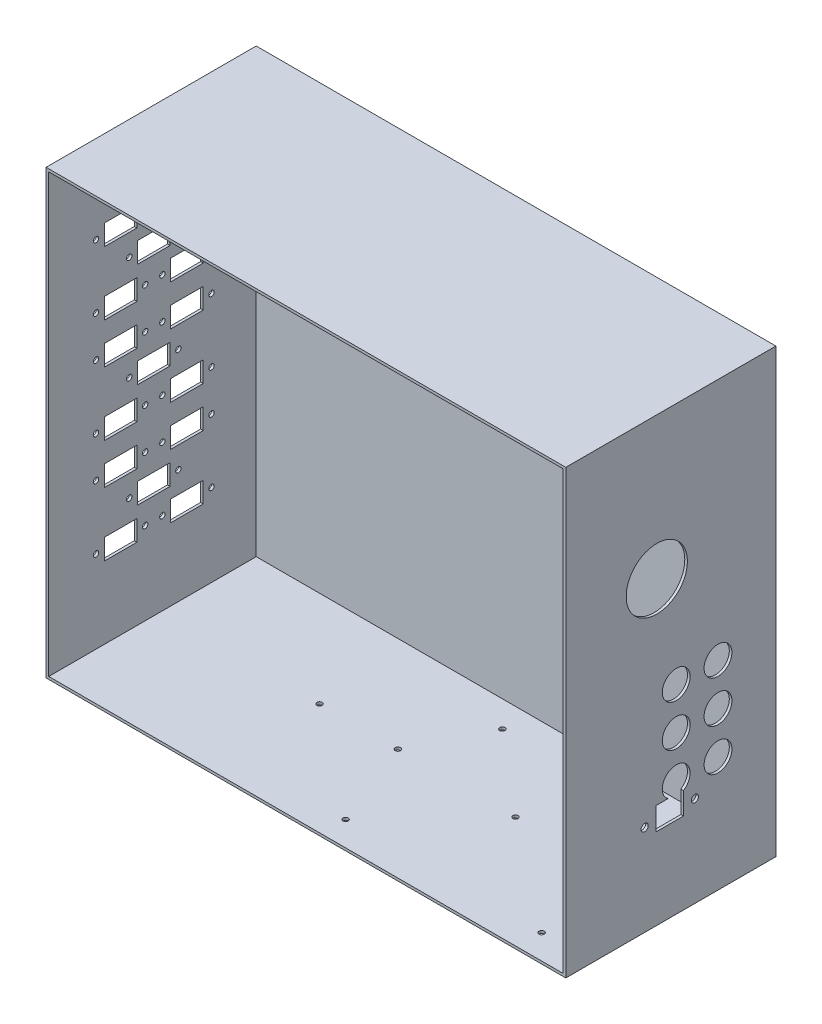
SolidWorks part; units mm, degrees
ref_plane "Front Plane" through (0, 0, 0) normal (0, 0, 1) x (1, 0, 0)
ref_plane "Top Plane" through (0, 0, 0) normal (0, 1, 0) x (1, 0, 0)
ref_plane "Right Plane" through (0, 0, 0) normal (1, 0, 0) x (0, 0, -1)
sketch "Sketch2" plane through (0, 0, 0) normal (0, 0, 1) x (1, 0, 0)
  line L1 (-149.225, 127) -> (149.225, 127)
  line L2 (-149.225, 127) -> (-149.225, -127)
  line L3 (-149.225, -127) -> (149.225, -127)
  line L4 (149.225, 127) -> (149.225, -127)
  line L5 (-149.225, 127) -> (149.225, -127) construction
  line L6 (-149.225, -127) -> (149.225, 127) construction
  point P0 (0, 0)
  dimension "D1" = 298.45
  dimension "D2" = 254
extrude "Boss-Extrude1" add sketch "Sketch2" along normal blind 120.65
shell "Shell1" thickness 1.5
sketch "Sketch3" plane through (149.225, 0, 0) normal (1, 0, 0) x (0, 0, -1)
  circle A0 centre (-57.2397, -60.6921) radius 8
  circle A1 centre (-33.2397, -60.6921) radius 8
  circle A2 centre (-33.2397, -36.6921) radius 8
  circle A3 centre (-33.2397, -12.6921) radius 8
  circle A4 centre (-57.2397, -36.6921) radius 8
  circle A5 centre (-57.2397, -12.6921) radius 8
  dimension "D1" = 16
  dimension "D2" = 2
  dimension "D3" = 3
extrude "PT Connector Cutouts" cut sketch "Sketch3" against normal up to next
sketch "Sketch4" plane through (-149.225, 0, 0) normal (-1, 0, 0) x (0, 0, 1)
  line L0 (41.275, 72.2563) -> (41.275, 84.0563) construction
  line L1 (31.925, 84.0563) -> (31.925, 72.2563)
  line L2 (31.925, 84.0563) -> (50.625, 84.0563)
  line L3 (50.625, 84.0563) -> (50.625, 72.2563)
  line L4 (31.925, 72.2563) -> (50.625, 72.2563)
  line L10 (22.225, -88.9) -> (98.425, -88.9) construction
  line L11 (22.225, -88.9) -> (22.225, 88.9) construction
  line L12 (22.225, 88.9) -> (98.425, 88.9) construction
  line L13 (98.425, -88.9) -> (98.425, 88.9) construction
  line L73 (120.65, 127) -> (0, 127) construction
  line L74 (0, 127) -> (0, -127) construction
  line L75 (31.925, 86.0563) -> (27.1625, 84.0563) construction
  line L81 (31.925, 70.2563) -> (50.625, 70.2563) construction
  line L83 (31.925, 86.0563) -> (50.625, 86.0563) construction
  line L84 (50.625, 86.0563) -> (55.3875, 84.0563) construction
  line L85 (31.925, 70.2563) -> (27.1625, 72.2563) construction
  line L86 (50.625, 70.2563) -> (55.3875, 72.2563) construction
  line L87 (31.925, 84.0563) -> (50.625, 84.0563) construction
  line L89 (31.925, 72.2563) -> (50.625, 72.2563) construction
  line L91 (31.925, 84.0563) -> (50.625, 84.0563) construction
  line L92 (24.275, 72.2563) -> (24.275, 84.0563) construction
  line L93 (24.275, 72.2563) -> (27.1625, 72.2563) construction
  line L94 (58.275, 72.2563) -> (58.275, 84.0563) construction
  line L95 (24.275, 84.0563) -> (27.1625, 84.0563) construction
  line L98 (55.3875, 84.0563) -> (58.275, 84.0563) construction
  line L99 (55.3875, 72.2563) -> (58.275, 72.2563) construction
  line L100 (31.925, 72.2563) -> (50.625, 72.2563) construction
  line L170 (120.65, -127) -> (0, -127) construction
  line L171 (70.025, 84.0563) -> (70.025, 72.2563)
  line L172 (70.025, 84.0563) -> (88.725, 84.0563)
  line L173 (88.725, 84.0563) -> (88.725, 72.2563)
  line L174 (70.025, 72.2563) -> (88.725, 72.2563)
  line L175 (79.375, 72.2563) -> (79.375, 84.0563) construction
  line L176 (70.025, 86.0563) -> (65.2625, 84.0563) construction
  line L177 (70.025, 70.2563) -> (88.725, 70.2563) construction
  line L178 (70.025, 86.0563) -> (88.725, 86.0563) construction
  line L179 (88.725, 86.0563) -> (93.4875, 84.0563) construction
  line L180 (70.025, 70.2563) -> (65.2625, 72.2563) construction
  line L181 (88.725, 70.2563) -> (93.4875, 72.2563) construction
  line L182 (70.025, 84.0563) -> (88.725, 84.0563) construction
  line L183 (70.025, 72.2563) -> (88.725, 72.2563) construction
  line L184 (70.025, 84.0563) -> (88.725, 84.0563) construction
  line L185 (62.375, 72.2563) -> (62.375, 84.0563) construction
  line L186 (62.375, 72.2563) -> (65.2625, 72.2563) construction
  line L187 (96.375, 72.2563) -> (96.375, 84.0563) construction
  line L188 (62.375, 84.0563) -> (65.2625, 84.0563) construction
  line L189 (93.4875, 84.0563) -> (96.375, 84.0563) construction
  line L190 (93.4875, 72.2563) -> (96.375, 72.2563) construction
  line L191 (70.025, 72.2563) -> (88.725, 72.2563) construction
  line L213 (70.025, 47.5438) -> (70.025, 35.7438)
  line L214 (70.025, 47.5438) -> (88.725, 47.5438)
  line L215 (88.725, 47.5438) -> (88.725, 35.7438)
  line L216 (70.025, 35.7438) -> (88.725, 35.7438)
  line L217 (79.375, 35.7438) -> (79.375, 47.5438) construction
  line L218 (70.025, 49.5438) -> (65.2625, 47.5438) construction
  line L219 (70.025, 33.7438) -> (88.725, 33.7438) construction
  line L220 (70.025, 49.5438) -> (88.725, 49.5438) construction
  line L221 (88.725, 49.5438) -> (93.4875, 47.5438) construction
  line L222 (70.025, 33.7438) -> (65.2625, 35.7438) construction
  line L223 (88.725, 33.7438) -> (93.4875, 35.7438) construction
  line L224 (70.025, 47.5438) -> (88.725, 47.5438) construction
  line L225 (70.025, 35.7438) -> (88.725, 35.7438) construction
  line L226 (70.025, 47.5438) -> (88.725, 47.5438) construction
  line L227 (62.375, 35.7438) -> (62.375, 47.5438) construction
  line L228 (62.375, 35.7438) -> (65.2625, 35.7438) construction
  line L229 (96.375, 35.7438) -> (96.375, 47.5438) construction
  line L230 (62.375, 47.5438) -> (65.2625, 47.5438) construction
  line L231 (93.4875, 47.5438) -> (96.375, 47.5438) construction
  line L232 (93.4875, 35.7438) -> (96.375, 35.7438) construction
  line L233 (70.025, 35.7438) -> (88.725, 35.7438) construction
  line L234 (70.025, 24.1563) -> (70.025, 12.3563)
  line L235 (70.025, 24.1563) -> (88.725, 24.1563)
  line L236 (88.725, 24.1563) -> (88.725, 12.3563)
  line L237 (70.025, 12.3563) -> (88.725, 12.3563)
  line L238 (79.375, 12.3563) -> (79.375, 24.1563) construction
  line L239 (70.025, 26.1563) -> (65.2625, 24.1563) construction
  line L240 (70.025, 10.3563) -> (88.725, 10.3563) construction
  line L241 (70.025, 26.1563) -> (88.725, 26.1563) construction
  line L242 (88.725, 26.1563) -> (93.4875, 24.1563) construction
  line L243 (70.025, 10.3563) -> (65.2625, 12.3563) construction
  line L244 (88.725, 10.3563) -> (93.4875, 12.3563) construction
  line L245 (70.025, 24.1563) -> (88.725, 24.1563) construction
  line L246 (70.025, 12.3563) -> (88.725, 12.3563) construction
  line L247 (70.025, 24.1563) -> (88.725, 24.1563) construction
  line L248 (62.375, 12.3563) -> (62.375, 24.1563) construction
  line L249 (62.375, 12.3563) -> (65.2625, 12.3563) construction
  line L250 (96.375, 12.3563) -> (96.375, 24.1563) construction
  line L251 (62.375, 24.1563) -> (65.2625, 24.1563) construction
  line L252 (93.4875, 24.1563) -> (96.375, 24.1563) construction
  line L253 (93.4875, 12.3563) -> (96.375, 12.3563) construction
  line L254 (70.025, 12.3563) -> (88.725, 12.3563) construction
  line L276 (70.025, -12.3562) -> (70.025, -24.1562)
  line L277 (70.025, -12.3562) -> (88.725, -12.3562)
  line L278 (88.725, -12.3562) -> (88.725, -24.1562)
  line L279 (70.025, -24.1562) -> (88.725, -24.1562)
  line L280 (79.375, -24.1562) -> (79.375, -12.3562) construction
  line L281 (70.025, -10.3562) -> (65.2625, -12.3562) construction
  line L282 (70.025, -26.1562) -> (88.725, -26.1562) construction
  line L283 (70.025, -10.3562) -> (88.725, -10.3562) construction
  line L284 (88.725, -10.3562) -> (93.4875, -12.3562) construction
  line L285 (70.025, -26.1562) -> (65.2625, -24.1562) construction
  line L286 (88.725, -26.1562) -> (93.4875, -24.1562) construction
  line L287 (70.025, -12.3562) -> (88.725, -12.3562) construction
  line L288 (70.025, -24.1562) -> (88.725, -24.1562) construction
  line L289 (70.025, -12.3562) -> (88.725, -12.3562) construction
  line L290 (62.375, -24.1562) -> (62.375, -12.3562) construction
  line L291 (62.375, -24.1562) -> (65.2625, -24.1562) construction
  line L292 (96.375, -24.1562) -> (96.375, -12.3562) construction
  line L293 (62.375, -12.3562) -> (65.2625, -12.3562) construction
  line L294 (93.4875, -12.3562) -> (96.375, -12.3562) construction
  line L295 (93.4875, -24.1562) -> (96.375, -24.1562) construction
  line L296 (70.025, -24.1562) -> (88.725, -24.1562) construction
  line L297 (70.025, -35.7437) -> (70.025, -47.5437)
  line L298 (70.025, -35.7437) -> (88.725, -35.7437)
  line L299 (88.725, -35.7437) -> (88.725, -47.5437)
  line L300 (70.025, -47.5437) -> (88.725, -47.5437)
  line L301 (79.375, -47.5437) -> (79.375, -35.7437) construction
  line L302 (70.025, -33.7437) -> (65.2625, -35.7437) construction
  line L303 (70.025, -49.5437) -> (88.725, -49.5437) construction
  line L304 (70.025, -33.7437) -> (88.725, -33.7437) construction
  line L305 (88.725, -33.7437) -> (93.4875, -35.7437) construction
  line L306 (70.025, -49.5437) -> (65.2625, -47.5437) construction
  line L307 (88.725, -49.5437) -> (93.4875, -47.5437) construction
  line L308 (70.025, -35.7437) -> (88.725, -35.7437) construction
  line L309 (70.025, -47.5437) -> (88.725, -47.5437) construction
  line L310 (70.025, -35.7437) -> (88.725, -35.7437) construction
  line L311 (62.375, -47.5437) -> (62.375, -35.7437) construction
  line L312 (62.375, -47.5437) -> (65.2625, -47.5437) construction
  line L313 (96.375, -47.5437) -> (96.375, -35.7437) construction
  line L314 (62.375, -35.7437) -> (65.2625, -35.7437) construction
  line L315 (93.4875, -35.7437) -> (96.375, -35.7437) construction
  line L316 (93.4875, -47.5437) -> (96.375, -47.5437) construction
  line L317 (70.025, -47.5437) -> (88.725, -47.5437) construction
  line L339 (70.025, -72.2562) -> (70.025, -84.0562)
  line L340 (70.025, -72.2562) -> (88.725, -72.2562)
  line L341 (88.725, -72.2562) -> (88.725, -84.0562)
  line L342 (70.025, -84.0562) -> (88.725, -84.0562)
  line L343 (79.375, -84.0562) -> (79.375, -72.2562) construction
  line L344 (70.025, -70.2562) -> (65.2625, -72.2562) construction
  line L345 (70.025, -86.0562) -> (88.725, -86.0562) construction
  line L346 (70.025, -70.2562) -> (88.725, -70.2562) construction
  line L347 (88.725, -70.2562) -> (93.4875, -72.2562) construction
  line L348 (70.025, -86.0562) -> (65.2625, -84.0562) construction
  line L349 (88.725, -86.0562) -> (93.4875, -84.0562) construction
  line L350 (70.025, -72.2562) -> (88.725, -72.2562) construction
  line L351 (70.025, -84.0562) -> (88.725, -84.0562) construction
  line L352 (70.025, -72.2562) -> (88.725, -72.2562) construction
  line L353 (62.375, -84.0562) -> (62.375, -72.2562) construction
  line L354 (62.375, -84.0562) -> (65.2625, -84.0562) construction
  line L355 (96.375, -84.0562) -> (96.375, -72.2562) construction
  line L356 (62.375, -72.2562) -> (65.2625, -72.2562) construction
  line L357 (93.4875, -72.2562) -> (96.375, -72.2562) construction
  line L358 (93.4875, -84.0562) -> (96.375, -84.0562) construction
  line L359 (70.025, -84.0562) -> (88.725, -84.0562) construction
  line L360 (50.975, 65.8) -> (50.975, 54)
  line L361 (50.975, 65.8) -> (69.675, 65.8)
  line L362 (69.675, 65.8) -> (69.675, 54)
  line L363 (50.975, 54) -> (69.675, 54)
  line L364 (60.325, 54) -> (60.325, 65.8) construction
  line L365 (50.975, 67.8) -> (46.2125, 65.8) construction
  line L366 (50.975, 52) -> (69.675, 52) construction
  line L367 (50.975, 67.8) -> (69.675, 67.8) construction
  line L368 (69.675, 67.8) -> (74.4375, 65.8) construction
  line L369 (50.975, 52) -> (46.2125, 54) construction
  line L370 (69.675, 52) -> (74.4375, 54) construction
  line L371 (50.975, 65.8) -> (69.675, 65.8) construction
  line L372 (50.975, 54) -> (69.675, 54) construction
  line L373 (50.975, 65.8) -> (69.675, 65.8) construction
  line L374 (43.325, 54) -> (43.325, 65.8) construction
  line L375 (43.325, 54) -> (46.2125, 54) construction
  line L376 (77.325, 54) -> (77.325, 65.8) construction
  line L377 (43.325, 65.8) -> (46.2125, 65.8) construction
  line L378 (74.4375, 65.8) -> (77.325, 65.8) construction
  line L379 (74.4375, 54) -> (77.325, 54) construction
  line L380 (50.975, 54) -> (69.675, 54) construction
  line L381 (31.925, 47.5438) -> (31.925, 35.7438)
  line L382 (31.925, 47.5438) -> (50.625, 47.5438)
  line L383 (50.625, 47.5438) -> (50.625, 35.7438)
  line L384 (31.925, 35.7438) -> (50.625, 35.7438)
  line L385 (41.275, 35.7438) -> (41.275, 47.5438) construction
  line L386 (31.925, 49.5438) -> (27.1625, 47.5438) construction
  line L387 (31.925, 33.7438) -> (50.625, 33.7438) construction
  line L388 (31.925, 49.5438) -> (50.625, 49.5438) construction
  line L389 (50.625, 49.5438) -> (55.3875, 47.5438) construction
  line L390 (31.925, 33.7438) -> (27.1625, 35.7438) construction
  line L391 (50.625, 33.7438) -> (55.3875, 35.7438) construction
  line L392 (31.925, 47.5438) -> (50.625, 47.5438) construction
  line L393 (31.925, 35.7438) -> (50.625, 35.7438) construction
  line L394 (31.925, 47.5438) -> (50.625, 47.5438) construction
  line L395 (24.275, 35.7438) -> (24.275, 47.5438) construction
  line L396 (24.275, 35.7438) -> (27.1625, 35.7438) construction
  line L397 (58.275, 35.7438) -> (58.275, 47.5438) construction
  line L398 (24.275, 47.5438) -> (27.1625, 47.5438) construction
  line L399 (55.3875, 47.5438) -> (58.275, 47.5438) construction
  line L400 (55.3875, 35.7438) -> (58.275, 35.7438) construction
  line L401 (31.925, 35.7438) -> (50.625, 35.7438) construction
  line L402 (31.925, 24.1563) -> (31.925, 12.3563)
  line L403 (31.925, 24.1563) -> (50.625, 24.1563)
  line L404 (50.625, 24.1563) -> (50.625, 12.3563)
  line L405 (31.925, 12.3563) -> (50.625, 12.3563)
  line L406 (41.275, 12.3563) -> (41.275, 24.1563) construction
  line L407 (31.925, 26.1563) -> (27.1625, 24.1563) construction
  line L408 (31.925, 10.3563) -> (50.625, 10.3563) construction
  line L409 (31.925, 26.1563) -> (50.625, 26.1563) construction
  line L410 (50.625, 26.1563) -> (55.3875, 24.1563) construction
  line L411 (31.925, 10.3563) -> (27.1625, 12.3563) construction
  line L412 (50.625, 10.3563) -> (55.3875, 12.3563) construction
  line L413 (31.925, 24.1563) -> (50.625, 24.1563) construction
  line L414 (31.925, 12.3563) -> (50.625, 12.3563) construction
  line L415 (31.925, 24.1563) -> (50.625, 24.1563) construction
  line L416 (24.275, 12.3563) -> (24.275, 24.1563) construction
  line L417 (24.275, 12.3563) -> (27.1625, 12.3563) construction
  line L418 (58.275, 12.3563) -> (58.275, 24.1563) construction
  line L419 (24.275, 24.1563) -> (27.1625, 24.1563) construction
  line L420 (55.3875, 24.1563) -> (58.275, 24.1563) construction
  line L421 (55.3875, 12.3563) -> (58.275, 12.3563) construction
  line L422 (31.925, 12.3563) -> (50.625, 12.3563) construction
  line L423 (50.975, 5.9) -> (50.975, -5.9)
  line L424 (50.975, 5.9) -> (69.675, 5.9)
  line L425 (69.675, 5.9) -> (69.675, -5.9)
  line L426 (50.975, -5.9) -> (69.675, -5.9)
  line L427 (60.325, -5.9) -> (60.325, 5.9) construction
  line L428 (50.975, 7.9) -> (46.2125, 5.9) construction
  line L429 (50.975, -7.9) -> (69.675, -7.9) construction
  line L430 (50.975, 7.9) -> (69.675, 7.9) construction
  line L431 (69.675, 7.9) -> (74.4375, 5.9) construction
  line L432 (50.975, -7.9) -> (46.2125, -5.9) construction
  line L433 (69.675, -7.9) -> (74.4375, -5.9) construction
  line L434 (50.975, 5.9) -> (69.675, 5.9) construction
  line L435 (50.975, -5.9) -> (69.675, -5.9) construction
  line L436 (50.975, 5.9) -> (69.675, 5.9) construction
  line L437 (43.325, -5.9) -> (43.325, 5.9) construction
  line L438 (43.325, -5.9) -> (46.2125, -5.9) construction
  line L439 (77.325, -5.9) -> (77.325, 5.9) construction
  line L440 (43.325, 5.9) -> (46.2125, 5.9) construction
  line L441 (74.4375, 5.9) -> (77.325, 5.9) construction
  line L442 (74.4375, -5.9) -> (77.325, -5.9) construction
  line L443 (50.975, -5.9) -> (69.675, -5.9) construction
  line L444 (31.925, -12.3562) -> (31.925, -24.1562)
  line L445 (31.925, -12.3562) -> (50.625, -12.3562)
  line L446 (50.625, -12.3562) -> (50.625, -24.1562)
  line L447 (31.925, -24.1562) -> (50.625, -24.1562)
  line L448 (41.275, -24.1562) -> (41.275, -12.3562) construction
  line L449 (31.925, -10.3562) -> (27.1625, -12.3562) construction
  line L450 (31.925, -26.1562) -> (50.625, -26.1562) construction
  line L451 (31.925, -10.3562) -> (50.625, -10.3562) construction
  line L452 (50.625, -10.3562) -> (55.3875, -12.3562) construction
  line L453 (31.925, -26.1562) -> (27.1625, -24.1562) construction
  line L454 (50.625, -26.1562) -> (55.3875, -24.1562) construction
  line L455 (31.925, -12.3562) -> (50.625, -12.3562) construction
  line L456 (31.925, -24.1562) -> (50.625, -24.1562) construction
  line L457 (31.925, -12.3562) -> (50.625, -12.3562) construction
  line L458 (24.275, -24.1562) -> (24.275, -12.3562) construction
  line L459 (24.275, -24.1562) -> (27.1625, -24.1562) construction
  line L460 (58.275, -24.1562) -> (58.275, -12.3562) construction
  line L461 (24.275, -12.3562) -> (27.1625, -12.3562) construction
  line L462 (55.3875, -12.3562) -> (58.275, -12.3562) construction
  line L463 (55.3875, -24.1562) -> (58.275, -24.1562) construction
  line L464 (31.925, -24.1562) -> (50.625, -24.1562) construction
  line L465 (31.925, -35.7437) -> (31.925, -47.5437)
  line L466 (31.925, -35.7437) -> (50.625, -35.7437)
  line L467 (50.625, -35.7437) -> (50.625, -47.5437)
  line L468 (31.925, -47.5437) -> (50.625, -47.5437)
  line L469 (41.275, -47.5437) -> (41.275, -35.7437) construction
  line L470 (31.925, -33.7437) -> (27.1625, -35.7437) construction
  line L471 (31.925, -49.5437) -> (50.625, -49.5437) construction
  line L472 (31.925, -33.7437) -> (50.625, -33.7437) construction
  line L473 (50.625, -33.7437) -> (55.3875, -35.7437) construction
  line L474 (31.925, -49.5437) -> (27.1625, -47.5437) construction
  line L475 (50.625, -49.5437) -> (55.3875, -47.5437) construction
  line L476 (31.925, -35.7437) -> (50.625, -35.7437) construction
  line L477 (31.925, -47.5437) -> (50.625, -47.5437) construction
  line L478 (31.925, -35.7437) -> (50.625, -35.7437) construction
  line L479 (24.275, -47.5437) -> (24.275, -35.7437) construction
  line L480 (24.275, -47.5437) -> (27.1625, -47.5437) construction
  line L481 (58.275, -47.5437) -> (58.275, -35.7437) construction
  line L482 (24.275, -35.7437) -> (27.1625, -35.7437) construction
  line L483 (55.3875, -35.7437) -> (58.275, -35.7437) construction
  line L484 (55.3875, -47.5437) -> (58.275, -47.5437) construction
  line L485 (31.925, -47.5437) -> (50.625, -47.5437) construction
  line L486 (50.975, -54) -> (50.975, -65.8)
  line L487 (50.975, -54) -> (69.675, -54)
  line L488 (69.675, -54) -> (69.675, -65.8)
  line L489 (50.975, -65.8) -> (69.675, -65.8)
  line L490 (60.325, -65.8) -> (60.325, -54) construction
  line L491 (50.975, -52) -> (46.2125, -54) construction
  line L492 (50.975, -67.8) -> (69.675, -67.8) construction
  line L493 (50.975, -52) -> (69.675, -52) construction
  line L494 (69.675, -52) -> (74.4375, -54) construction
  line L495 (50.975, -67.8) -> (46.2125, -65.8) construction
  line L496 (69.675, -67.8) -> (74.4375, -65.8) construction
  line L497 (50.975, -54) -> (69.675, -54) construction
  line L498 (50.975, -65.8) -> (69.675, -65.8) construction
  line L499 (50.975, -54) -> (69.675, -54) construction
  line L500 (43.325, -65.8) -> (43.325, -54) construction
  line L501 (43.325, -65.8) -> (46.2125, -65.8) construction
  line L502 (77.325, -65.8) -> (77.325, -54) construction
  line L503 (43.325, -54) -> (46.2125, -54) construction
  line L504 (74.4375, -54) -> (77.325, -54) construction
  line L505 (74.4375, -65.8) -> (77.325, -65.8) construction
  line L506 (50.975, -65.8) -> (69.675, -65.8) construction
  line L507 (31.925, -72.2562) -> (31.925, -84.0562)
  line L508 (31.925, -72.2562) -> (50.625, -72.2562)
  line L509 (50.625, -72.2562) -> (50.625, -84.0562)
  line L510 (31.925, -84.0562) -> (50.625, -84.0562)
  line L511 (41.275, -84.0562) -> (41.275, -72.2562) construction
  line L512 (31.925, -70.2562) -> (27.1625, -72.2562) construction
  line L513 (31.925, -86.0562) -> (50.625, -86.0562) construction
  line L514 (31.925, -70.2562) -> (50.625, -70.2562) construction
  line L515 (50.625, -70.2562) -> (55.3875, -72.2562) construction
  line L516 (31.925, -86.0562) -> (27.1625, -84.0562) construction
  line L517 (50.625, -86.0562) -> (55.3875, -84.0562) construction
  line L518 (31.925, -72.2562) -> (50.625, -72.2562) construction
  line L519 (31.925, -84.0562) -> (50.625, -84.0562) construction
  line L520 (31.925, -72.2562) -> (50.625, -72.2562) construction
  line L521 (24.275, -84.0562) -> (24.275, -72.2562) construction
  line L522 (24.275, -84.0562) -> (27.1625, -84.0562) construction
  line L523 (58.275, -84.0562) -> (58.275, -72.2562) construction
  line L524 (24.275, -72.2562) -> (27.1625, -72.2562) construction
  line L525 (55.3875, -72.2562) -> (58.275, -72.2562) construction
  line L526 (55.3875, -84.0562) -> (58.275, -84.0562) construction
  line L527 (31.925, -84.0562) -> (50.625, -84.0562) construction
  circle A0 centre (55.3875, 78.1563) radius 1.55
  circle A1 centre (27.1625, 78.1563) radius 1.55
  circle A2 centre (93.4875, 78.1563) radius 1.55
  circle A3 centre (65.2625, 78.1563) radius 1.55
  circle A6 centre (93.4875, 41.6438) radius 1.55
  circle A7 centre (65.2625, 41.6438) radius 1.55
  circle A8 centre (93.4875, 18.2563) radius 1.55
  circle A9 centre (65.2625, 18.2563) radius 1.55
  circle A12 centre (93.4875, -18.2562) radius 1.55
  circle A13 centre (65.2625, -18.2562) radius 1.55
  circle A14 centre (93.4875, -41.6437) radius 1.55
  circle A15 centre (65.2625, -41.6437) radius 1.55
  circle A18 centre (93.4875, -78.1562) radius 1.55
  circle A19 centre (65.2625, -78.1562) radius 1.55
  circle A20 centre (74.4375, 59.9) radius 1.55
  circle A21 centre (46.2125, 59.9) radius 1.55
  circle A22 centre (55.3875, 41.6438) radius 1.55
  circle A23 centre (27.1625, 41.6438) radius 1.55
  circle A24 centre (55.3875, 18.2563) radius 1.55
  circle A25 centre (27.1625, 18.2563) radius 1.55
  circle A26 centre (74.4375, 0) radius 1.55
  circle A27 centre (46.2125, 0) radius 1.55
  circle A28 centre (55.3875, -18.2562) radius 1.55
  circle A29 centre (27.1625, -18.2562) radius 1.55
  circle A30 centre (55.3875, -41.6437) radius 1.55
  circle A31 centre (27.1625, -41.6437) radius 1.55
  circle A32 centre (74.4375, -59.9) radius 1.55
  circle A33 centre (46.2125, -59.9) radius 1.55
  circle A34 centre (55.3875, -78.1562) radius 1.55
  circle A35 centre (27.1625, -78.1562) radius 1.55
  point P0 (41.275, 78.1563)
  point P10 (41.275, 78.1563)
  point P14 (79.375, 78.1563)
  point P30 (79.375, 78.1563)
  point P32 (79.375, 78.1563)
  point P33 (79.375, 78.1563)
  point P37 (79.375, 78.1563)
  point P76 (79.375, 41.6438)
  point P86 (79.375, 41.6438)
  point P88 (79.375, 41.6438)
  point P89 (79.375, 41.6438)
  point P93 (79.375, 41.6438)
  point P103 (79.375, 18.2563)
  point P113 (79.375, 18.2563)
  point P115 (79.375, 18.2563)
  point P116 (79.375, 18.2563)
  point P120 (79.375, 18.2563)
  point P141 (41.275, 78.1563)
  point P142 (41.275, 78.1563)
  point P146 (41.275, 78.1563)
  point P174 (79.375, -18.2562)
  point P184 (79.375, -18.2562)
  point P186 (79.375, -18.2562)
  point P187 (79.375, -18.2562)
  point P191 (79.375, -18.2562)
  point P201 (79.375, -41.6437)
  point P211 (79.375, -41.6437)
  point P213 (79.375, -41.6437)
  point P214 (79.375, -41.6437)
  point P218 (79.375, -41.6437)
  point P255 (79.375, -78.1562)
  point P265 (79.375, -78.1562)
  point P267 (79.375, -78.1562)
  point P268 (79.375, -78.1562)
  point P272 (79.375, -78.1562)
  point P282 (60.325, 59.9)
  point P292 (60.325, 59.9)
  point P294 (60.325, 59.9)
  point P295 (60.325, 59.9)
  point P299 (60.325, 59.9)
  point P309 (41.275, 41.6438)
  point P319 (41.275, 41.6438)
  point P321 (41.275, 41.6438)
  point P322 (41.275, 41.6438)
  point P326 (41.275, 41.6438)
  point P336 (41.275, 18.2563)
  point P346 (41.275, 18.2563)
  point P348 (41.275, 18.2563)
  point P349 (41.275, 18.2563)
  point P353 (41.275, 18.2563)
  point P363 (60.325, 0)
  point P373 (60.325, 0)
  point P375 (60.325, 0)
  point P376 (60.325, 0)
  point P380 (60.325, 0)
  point P390 (41.275, -18.2562)
  point P400 (41.275, -18.2562)
  point P402 (41.275, -18.2562)
  point P403 (41.275, -18.2562)
  point P407 (41.275, -18.2562)
  point P417 (41.275, -41.6437)
  point P427 (41.275, -41.6437)
  point P429 (41.275, -41.6437)
  point P430 (41.275, -41.6437)
  point P434 (41.275, -41.6437)
  point P444 (60.325, -59.9)
  point P454 (60.325, -59.9)
  point P456 (60.325, -59.9)
  point P457 (60.325, -59.9)
  point P461 (60.325, -59.9)
  point P471 (41.275, -78.1562)
  point P481 (41.275, -78.1562)
  point P483 (41.275, -78.1562)
  point P484 (41.275, -78.1562)
  point P488 (41.275, -78.1562)
  dimension "D1" = 18.7
  dimension "D4" = 4.7625
  dimension "D5" = 177.8
  dimension "D6" = 76.2
  dimension "D9" = 38.1
  dimension "D10" = 22.225
  dimension "D11" = 34
  dimension "D12" = 15.8
  dimension "D13" = 18.7
  dimension "D14" = 4.7625
extrude "Solenoid Connector Cutouts" cut sketch "Sketch4" against normal up to next (1.5 mm away)
sketch "Punchout Panel" plane through (-149.225, 0, 0) normal (-1, 0, 0) x (0, 0, 1)
  line L1 (98.425, 88.9) -> (22.225, 88.9) construction
  line L2 (98.425, 88.9) -> (98.425, -88.9) construction
  line L3 (98.425, -88.9) -> (22.225, -88.9) construction
  line L4 (22.225, 88.9) -> (22.225, -88.9) construction
  point P0 (60.325, 0)
sketch "Sketch5" plane through (0, -127, 127) normal (0, 1, 0) x (-1, 0, 0)
  line L1 (-126.2359, -15.4623) -> (-51.2359, -15.4623) construction
  line L2 (-126.2359, -15.4623) -> (-126.2359, -115.4623) construction
  line L3 (-126.2359, -115.4623) -> (-51.2359, -115.4623) construction
  line L4 (-51.2359, -15.4623) -> (-51.2359, -115.4623) construction
  line L5 (-13.675, -15.4623) -> (61.325, -15.4623) construction
  line L6 (-13.675, -15.4623) -> (-13.675, -115.4623) construction
  line L7 (-13.675, -115.4623) -> (61.325, -115.4623) construction
  line L8 (61.325, -15.4623) -> (61.325, -115.4623) construction
  circle A0 centre (-121.2359, -20.4623) radius 1.524
  circle A4 centre (-56.2359, -70.4623) radius 1.524
  circle A5 centre (-121.2359, -110.4623) radius 1.524
  circle A7 centre (-101.2359, -70.4623) radius 1.524
  circle A8 centre (-8.675, -20.4623) radius 1.524
  circle A9 centre (56.325, -70.4623) radius 1.524
  circle A10 centre (-8.675, -110.4623) radius 1.524
  circle A11 centre (11.325, -70.4623) radius 1.524
  point P0 (11.325, -69.9518)
  point P24 (-32.1293, -84.0848)
  point P25 (54.7658, -112.5631)
  point P26 (59.8773, -111.1027)
  dimension "D3" = 3.048
  dimension "D6" = 3.048
  dimension "D8" = 3.048
  dimension "D9" = 3.048
  dimension "D16" = 3.048
  dimension "D19" = 3.048
  dimension "D21" = 3.048
  dimension "D22" = 3.048
  dimension "D1" = 75
  dimension "D2" = 100
  dimension "D4" = 5
  dimension "D5" = 5
  dimension "D7" = 5
  dimension "D10" = 55
  dimension "D11" = 45
  dimension "D12" = 5
  dimension "D13" = 5
  dimension "D14" = 75
  dimension "D15" = 100
  dimension "D17" = 5
  dimension "D18" = 5
  dimension "D20" = 5
  dimension "D23" = 55
  dimension "D24" = 45
  dimension "D25" = 5
  dimension "D26" = 5
extrude "PCB Mounting Holes" cut sketch "Sketch5" along normal up to surface (1.5 mm away) up to face at (0, -125.5, 61.075)
sketch "Sketch6" plane through (149.225, 0, 0) normal (1, 0, 0) x (0, 0, -1)
  circle A0 centre (-68.3871, 45.4363) radius 17.5741
extrude "Cut-Extrude2" cut sketch "Sketch6" against normal up to surface (1.5 mm away) up to face at (147.725, -36.6921, 65.2397)
sketch "Sketch7" plane through (0, 0, 0) normal (0, 0, -1) x (-1, 0, 0)
  line L1 (93.8671, 0) -> (20.7994, 0) construction
  line L2 (93.8671, 0) -> (93.8671, 96.9752) construction
  line L3 (93.8671, 96.9752) -> (20.7994, 96.9752) construction
  line L4 (20.7994, 0) -> (20.7994, 96.9752) construction
  circle A0 centre (75.1913, 21.7568) radius 10.7357
  circle A1 centre (46.3682, 57.1323) radius 9.2127
  circle A2 centre (69.9508, 74.9932) radius 5.2039
  circle A3 centre (46.3682, 28.6857) radius 2.4407
extrude "Cut-Extrude3" cut sketch "Sketch7" against normal up to surface (1.5 mm away) up to face at (0, 0, 1.5)
sketch "Sketch8" plane through (149.225, 0, 0) normal (-1, 0, 0) x (0, 0, 1)
  line L18 (71.7989, -69.8033) -> (78.9109, -69.8033) construction
  line L19 (50.0819, -85.9323) -> (71.7989, -85.9323) construction
  line L34 (50.0819, -85.9323) -> (50.0819, -79.8363) construction
  line L35 (50.0819, -63.7073) -> (71.7989, -63.7073) construction
  line L40 (71.7989, -85.9323) -> (71.7989, -79.8363) construction
  line L41 (71.7989, -79.8363) -> (78.9109, -79.8363) construction
  line L42 (50.0819, -69.8033) -> (50.0819, -63.7073) construction
  line L43 (42.9699, -69.8033) -> (50.0819, -69.8033) construction
  line L44 (42.9699, -69.8033) -> (42.9699, -79.8363) construction
  line L45 (42.9699, -79.8363) -> (50.0819, -79.8363) construction
  line L46 (78.9109, -69.8033) -> (78.9109, -79.8363) construction
  line L47 (71.7989, -69.8033) -> (71.7989, -63.7073) construction
  line L48 (60.9404, -63.7073) -> (60.9404, -85.9323) construction
  line L49 (42.9699, -74.8198) -> (78.9109, -74.8198) construction
  line L50 (53.0664, -67.1512) -> (68.8144, -67.1512)
  line L51 (53.0664, -67.1512) -> (53.0664, -80.2322)
  line L52 (53.0664, -80.2322) -> (68.8144, -80.2322)
  line L53 (68.8144, -67.1512) -> (68.8144, -80.2322)
  circle A5 centre (46.5259, -74.8198) radius 2.0638
  circle A6 centre (75.3549, -74.8198) radius 2.0638
  dimension "D5" = 4.1275
  dimension "D1" = 21.717
  dimension "D2" = 22.225
  dimension "D3" = 35.941
  dimension "D4" = 10.033
  dimension "D6" = 13.081
  dimension "D7" = 15.748
  dimension "D8" = 5.7001
extrude "Cut-Extrude4" cut sketch "Sketch8" along normal up to surface (1.5 mm away) up to face at (147.725, 45.4363, 85.9612)
